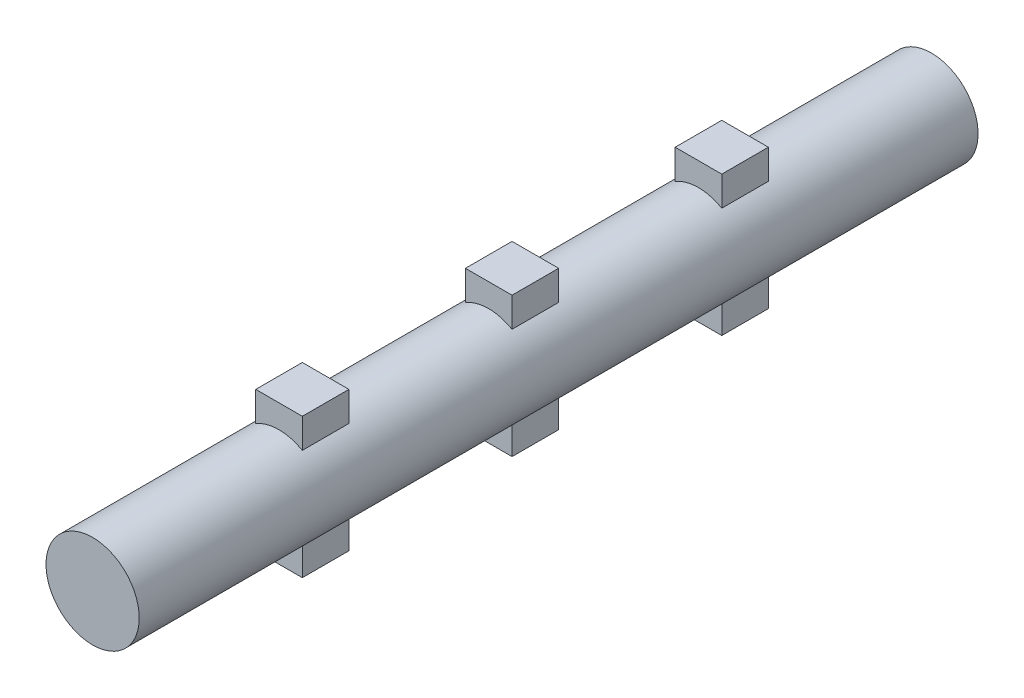
SolidWorks part; units mm, degrees
ref_plane "Front Plane" through (0, 0, 0) normal (0, 0, 1) x (1, 0, 0)
ref_plane "Top Plane" through (0, 0, 0) normal (0, 1, 0) x (1, 0, 0)
ref_plane "Right Plane" through (0, 0, 0) normal (1, 0, 0) x (0, 0, -1)
sketch "Sketch1" plane through (0, 0, 0) normal (0, 0, 1) x (1, 0, 0)
  circle A0 centre (0, 0) radius 5
  dimension "D1" = 10
extrude "Boss-Extrude1" add sketch "Sketch1" along normal blind 25
sketch "Sketch2" plane through (0, 0, 25) normal (0, 0, 1) x (1, 0, 0)
  line L1 (-2.5, -7.5) -> (2.5, -7.5)
  line L2 (-2.5, -7.5) -> (-2.5, 7.5)
  line L3 (-2.5, 7.5) -> (2.5, 7.5)
  line L4 (2.5, -7.5) -> (2.5, 7.5)
  line L5 (-2.5, -7.5) -> (2.5, 7.5) construction
  line L6 (-2.5, 7.5) -> (2.5, -7.5) construction
  point P0 (0, 0)
  dimension "D1" = 15
  dimension "D2" = 5
extrude "Boss-Extrude2" add sketch "Sketch2" against normal blind 5
sketch "Sketch3" plane through (0, 0, 0) normal (0, 0, -1) x (-1, 0, 0)
  line L1 (-2.5, -7.5) -> (2.5, -7.5)
  line L2 (-2.5, -7.5) -> (-2.5, 7.5)
  line L3 (-2.5, 7.5) -> (2.5, 7.5)
  line L4 (2.5, -7.5) -> (2.5, 7.5)
  line L5 (-2.5, -7.5) -> (2.5, 7.5) construction
  line L6 (-2.5, 7.5) -> (2.5, -7.5) construction
  point P0 (0, 0)
  dimension "D1" = 15
  dimension "D2" = 5
extrude "Boss-Extrude3" add sketch "Sketch3" against normal blind 2.5
sketch "Sketch5" plane through (0, 0, 0) normal (0, 0, -1) x (-1, 0, 0)
  line L0 (2.5, 4.3301) -> (2.5, 7.5) construction
  line L1 (-2.5, -7.5) -> (2.5, -7.5)
  line L2 (-2.5, -7.5) -> (-2.5, 7.5)
  line L3 (-2.5, 7.5) -> (2.5, 7.5)
  line L4 (2.5, -7.5) -> (2.5, 7.5)
  line L5 (-2.5, -7.5) -> (2.5, 7.5) construction
  line L6 (-2.5, 7.5) -> (2.5, -7.5) construction
  point P0 (0, 0)
extrude "Boss-Extrude5" add sketch "Sketch5" along normal blind 2.5
sketch "Sketch6" plane through (0, 0, 0) normal (0, 0, -1) x (-1, 0, 0)
  circle A0 centre (0, 0) radius 5
extrude "Boss-Extrude6" add sketch "Sketch6" along normal blind 25
sketch "Sketch7" plane through (0, 0, -25) normal (0, 0, -1) x (-1, 0, 0)
  line L1 (2.5, -7.5) -> (-2.5, -7.5)
  line L2 (2.5, -7.5) -> (2.5, 7.5)
  line L3 (2.5, 7.5) -> (-2.5, 7.5)
  line L4 (-2.5, -7.5) -> (-2.5, 7.5)
  line L5 (2.5, -7.5) -> (-2.5, 7.5) construction
  line L6 (2.5, 7.5) -> (-2.5, -7.5) construction
  point P0 (0, 0)
  dimension "D1" = 15
  dimension "D2" = 5
extrude "Boss-Extrude7" add sketch "Sketch7" against normal blind 5
hole_wizard "Ø5.0mm Dowel Hole1" positions "Sketch11" profile "Sketch12" hole size "Ø5.0" standard "ANSI Metric" end condition through all
sketch "Sketch11" plane through (0, 0, 25) normal (0, 0, 1) x (1, 0, 0)
  point P0 (0, 0)
sketch "Sketch12" plane through (0, 0, 25) normal (1, 0, 0) x (0, -1, 0)
  line L0 (0, 0) -> (0, 50)
  line L1 (0, 50) -> (2.5, 50)
  line L2 (2.5, 50) -> (2.5, 0)
  line L5 (2.5, 0) -> (0, 0)
  line L11 (0, -6.35) -> (0, 107.95) construction
  dimension "Thru Hole Dia." = 5
  dimension "Thru Hole Depth" = 50
sketch "Sketch14" plane through (0, 0, -25) normal (0, 0, -1) x (-1, 0, 0)
  circle A0 centre (0, 0) radius 5
extrude "Boss-Extrude8" add sketch "Sketch14" along normal blind 20
sketch "Sketch15" plane through (0, 0, 25) normal (0, 0, 1) x (1, 0, 0)
  circle A0 centre (0, 0) radius 5
extrude "Boss-Extrude9" add sketch "Sketch15" along normal blind 20
